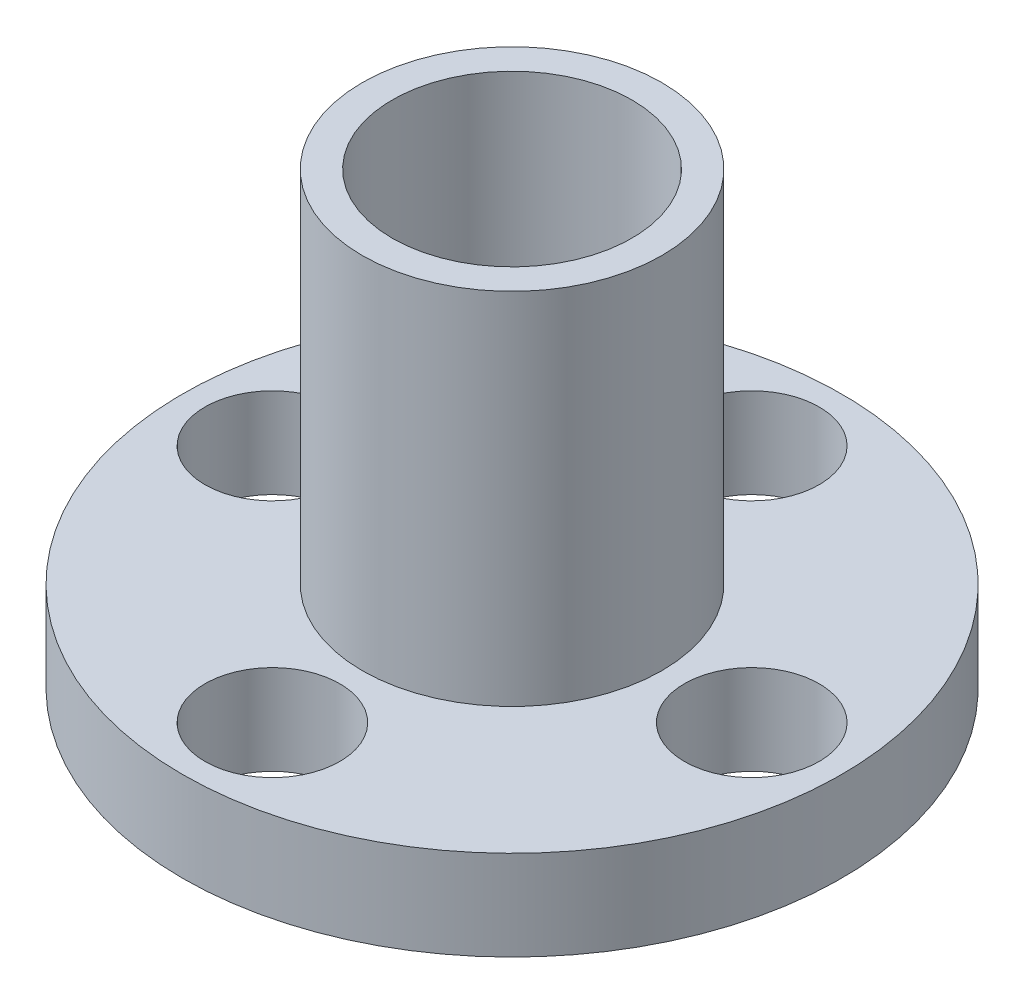
SolidWorks part; units mm, degrees
material "Brass"
ref_plane "Front Plane" through (0, 0, 0) normal (0, 0, 1) x (1, 0, 0)
ref_plane "Top Plane" through (0, 0, 0) normal (0, 1, 0) x (1, 0, 0)
ref_plane "Right Plane" through (0, 0, 0) normal (1, 0, 0) x (0, 0, -1)
sketch "Sketch1" plane through (0, 0, 0) normal (0, 1, 0) x (1, 0, 0)
  circle A0 centre (0, 0) radius 11
  dimension "D1" = 22
extrude "Boss-Extrude1" add sketch "Sketch1" along normal blind 3
sketch "Sketch2" plane through (0, 3, 0) normal (0, 1, 0) x (1, 0, 0)
  circle A0 centre (0, 0) radius 5
  dimension "D1" = 10
extrude "Boss-Extrude2" add sketch "Sketch2" along normal blind 12
sketch "Sketch3" plane through (0, 15, 0) normal (0, 1, 0) x (1, 0, 0)
  circle A0 centre (0, 0) radius 4
  dimension "D1" = 8
extrude "Cut-Extrude1" cut sketch "Sketch3" against normal through all
sketch "Sketch4" plane through (0, 3, 0) normal (0, 1, 0) x (1, 0, 0)
  circle A0 centre (8, 0) radius 2.25
  circle A1 centre (0, 8) radius 2.25
  circle A2 centre (-8, 0) radius 2.25
  circle A3 centre (0, -8) radius 2.25
  circle A4 centre (0, 0) radius 8 construction
  dimension "D1" = 4.5
  dimension "D2" = 16
extrude "Cut-Extrude2" cut sketch "Sketch4" against normal through all
